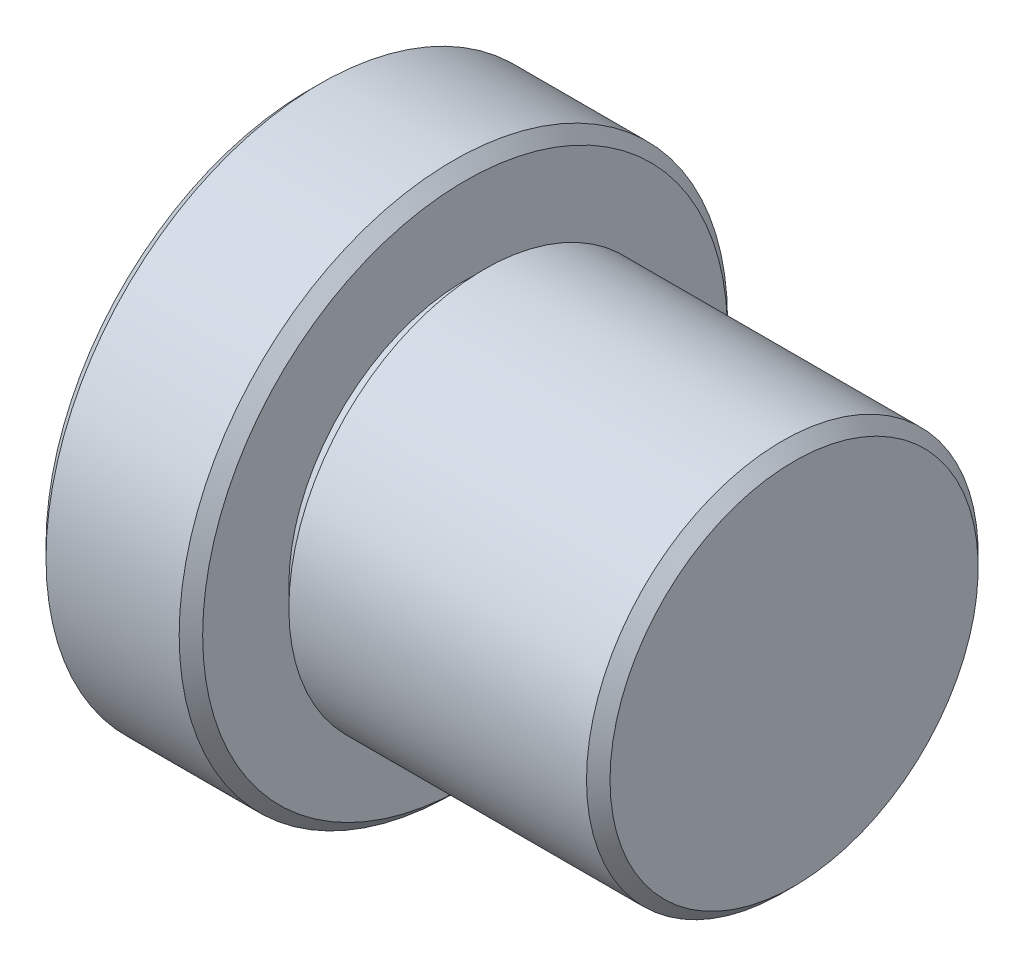
SolidWorks part; units mm, degrees
ref_plane "Plan de face" through (0, 0, 0) normal (0, 0, 1) x (1, 0, 0)
ref_plane "Plan de dessus" through (0, 0, 0) normal (0, 1, 0) x (1, 0, 0)
ref_plane "Plan de droite" through (0, 0, 0) normal (1, 0, 0) x (0, 0, -1)
sketch "Esquisse1" plane through (0, 0, 0) normal (0, 0, 1) x (1, 0, 0)
  line L0 (-14.2068, 0) -> (-0.2068, 0) construction
  line L1 (0, 0) -> (0, 6.7)
  line L2 (0.3, 7) -> (3.7, 7)
  line L3 (4, 6.7) -> (4, 4.5)
  line L4 (4, 4.5) -> (4.5, 4.5)
  line L5 (4.5, 4.5) -> (4.5, 5)
  line L6 (4.5, 5) -> (12.1, 5)
  line L7 (0, 6.7) -> (0.3, 7)
  line L8 (12.4, 4.7) -> (12.4, 0)
  line L9 (12.4, 0) -> (0, 0)
  line L10 (3.7, 7) -> (4, 6.7)
  line L11 (12.1, 5) -> (12.4, 4.7)
  point P4 (0, 7)
  point P6 (4, 7)
  point P11 (12.4, 5)
  dimension "D1" = 12.4
  dimension "D2" = 14
  dimension "D3" = 10
  dimension "D4" = 0.5
  dimension "D5" = 4
  dimension "D6" = 0.5
  dimension "D9" = 0.3
  dimension "D10" = 0.3
  dimension "D11" = 0.3
revolve "Révolution1" add sketch "Esquisse1" angle 360 about L0
cosmetic thread "Représentation de filetage1" parameters "D2"=9
sketch "Esquisse2" plane through (0, 0, 0) normal (-1, 0, 0) x (0, 0, 1)
  line L0 (-1.4434, 2.5) -> (1.4434, 2.5)
  line L1 (1.4434, 2.5) -> (2.8868, 0)
  line L2 (2.8868, 0) -> (1.4434, -2.5)
  line L3 (1.4434, -2.5) -> (-1.4434, -2.5)
  line L4 (-1.4434, -2.5) -> (-2.8868, 0)
  line L5 (-2.8868, 0) -> (-1.4434, 2.5)
  circle A0 centre (0, 0) radius 2.8868 construction
  dimension "D1" = 5
  dimension "D2" = 5
extrude "Enlèv. mat.-Extru.1" cut sketch "Esquisse2" against normal blind 8
